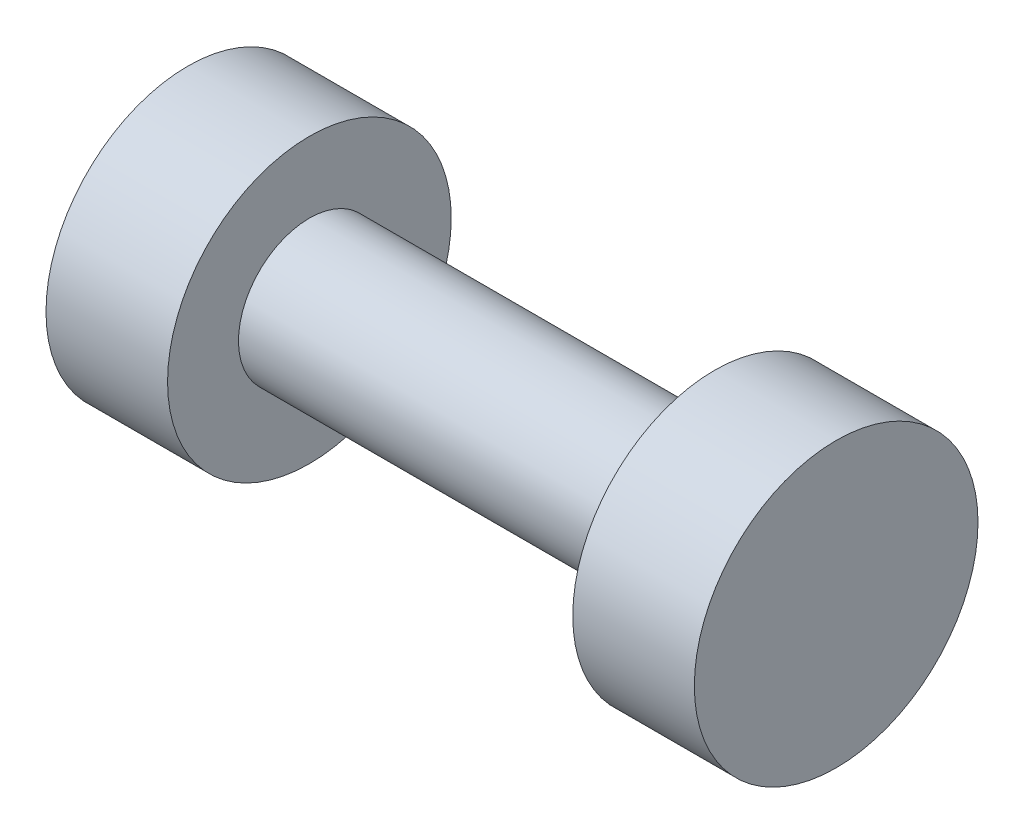
SolidWorks part; units mm, degrees
ref_plane "Front Plane" through (0, 0, 0) normal (0, 0, 1) x (1, 0, 0)
ref_plane "Top Plane" through (0, 0, 0) normal (0, 1, 0) x (1, 0, 0)
ref_plane "Right Plane" through (0, 0, 0) normal (1, 0, 0) x (0, 0, -1)
sketch "Sketch1" plane through (0, 0, 0) normal (0, 0, 1) x (1, 0, 0)
  line L0 (0, 0) -> (-124.2911, 0) construction
  line L1 (0, 0) -> (80, 0) construction
  line L2 (-80, 0) -> (-80, 35)
  line L3 (-80, 35) -> (-50, 35)
  line L4 (-50, 35) -> (-50, 17.5)
  line L5 (-50, 17.5) -> (50, 17.5)
  line L6 (50, 17.5) -> (50, 35)
  line L7 (50, 35) -> (80, 35)
  line L8 (80, 35) -> (80, 0)
  line L9 (80, 0) -> (-80, 0)
  point P9 (0, 0)
  point P12 (-80, 17.5)
  dimension "D1" = 35
  dimension "D2" = 30
  dimension "D3" = 100
  dimension "D4" = 30
revolve "Revolve1" add sketch "Sketch1" angle 360 about L9
